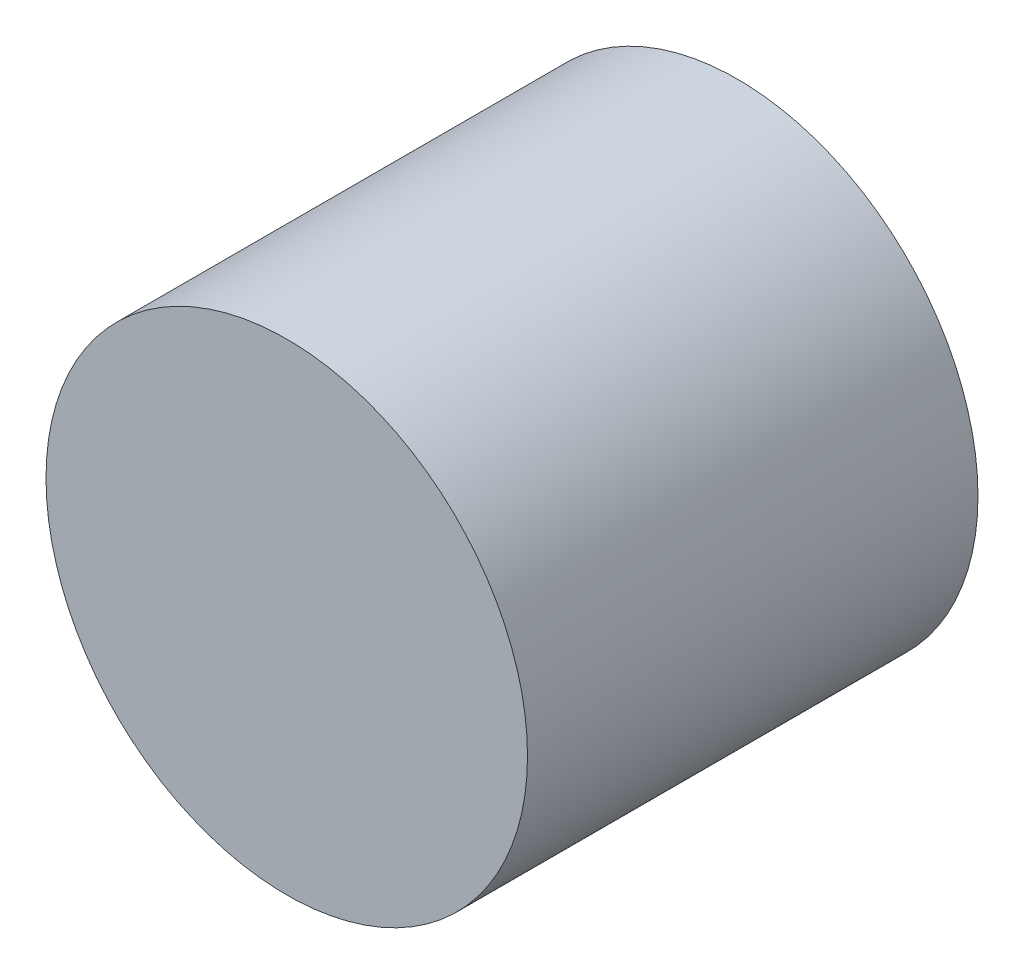
SolidWorks part; units mm, degrees
ref_plane "Front Plane" through (0, 0, 0) normal (0, 0, 1) x (1, 0, 0)
ref_plane "Top Plane" through (0, 0, 0) normal (0, 1, 0) x (1, 0, 0)
ref_plane "Right Plane" through (0, 0, 0) normal (1, 0, 0) x (0, 0, -1)
sketch "Sketch1" plane through (0, 0, 0) normal (0, 0, 1) x (1, 0, 0)
  circle A0 centre (0, 0) radius 2.5
  dimension "D1" = 5
extrude "Boss-Extrude1" add sketch "Sketch1" along normal blind 4.6777
equation "\"LA_width\"=4.67766733"
equation "\"D1@Boss-Extrude1\"=\"LA_width\""
equation "\"LA_length\"=50.00000000"
equation "\"LA_height\"=6.76462661"
equation "\"radius_pin\"=2.33883367"
